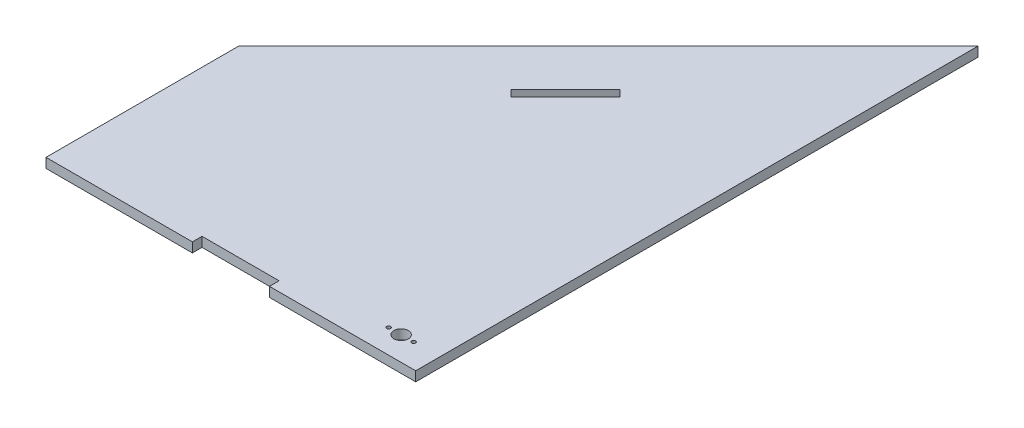
SolidWorks part; units mm, degrees
ref_plane "Front Plane" through (0, 0, 0) normal (0, 0, 1) x (1, 0, 0)
ref_plane "Top Plane" through (0, 0, 0) normal (0, 1, 0) x (1, 0, 0)
ref_plane "Right Plane" through (0, 0, 0) normal (1, 0, 0) x (0, 0, -1)
sketch "Sketch1" plane through (0, 0, 0) normal (0, 1, 0) x (1, 0, 0)
  line L0 (0, 63.5) -> (121.8717, 185.3717)
  line L1 (0, 0) -> (31.75, 0)
  line L2 (0, 0) -> (0, 63.5)
  line L3 (63.5, 0) -> (121.8717, 0)
  line L4 (121.8717, 0) -> (121.8717, 121.5492)
  line L6 (121.8717, 121.5492) -> (121.8717, 185.3717)
  line L9 (63.5, 0) -> (31.75, 0)
  dimension "D1" = 135
  dimension "D2" = 31.75
  dimension "D3" = 31.75
  dimension "D4" = 63.5
extrude "Boss-Extrude1" add sketch "Sketch1" along normal blind 3.175
sketch "Sketch2" plane through (0, 3.175, 0) normal (0, 1, 0) x (1, 0, 0)
  line L0 (57.2403, 96.0623) -> (59.4853, 93.8172)
  line L1 (59.4853, 93.8172) -> (77.4458, 111.7777)
  line L2 (77.4458, 111.7777) -> (75.2008, 114.0228)
  line L3 (75.2008, 114.0228) -> (57.2403, 96.0623)
  line L5 (105.0442, 7.8994) -> (113.2992, 7.8994) construction
  line L6 (121.8717, 0) -> (121.8717, 185.3717) construction
  line L7 (0, 0) -> (121.8717, 0) construction
  line L8 (0, 63.5) -> (0, 0) construction
  line L9 (48.26, 0) -> (73.66, 0)
  line L10 (48.26, 0) -> (48.26, 3.175)
  line L11 (48.26, 3.175) -> (73.66, 3.175)
  line L12 (73.66, 0) -> (73.66, 3.175)
  circle A0 centre (109.1717, 7.8994) radius 2.3813
  circle A1 centre (105.0442, 7.8994) radius 0.635
  circle A2 centre (113.2992, 7.8994) radius 0.635
  dimension "D4" = 4.7625
  dimension "D5" = 1.27
  dimension "D6" = 1.27
  dimension "D1" = 3.175
  dimension "D2" = 25.4
  dimension "D3" = 63.5
  dimension "D7" = 8.255
  dimension "D8" = 4.1275
  dimension "D9" = 12.7
  dimension "D10" = 7.8994
  dimension "D11" = 3.175
  dimension "D12" = 48.26
  dimension "D13" = 25.4
extrude "Cut-Extrude1" cut sketch "Sketch2" against normal blind 3.175
